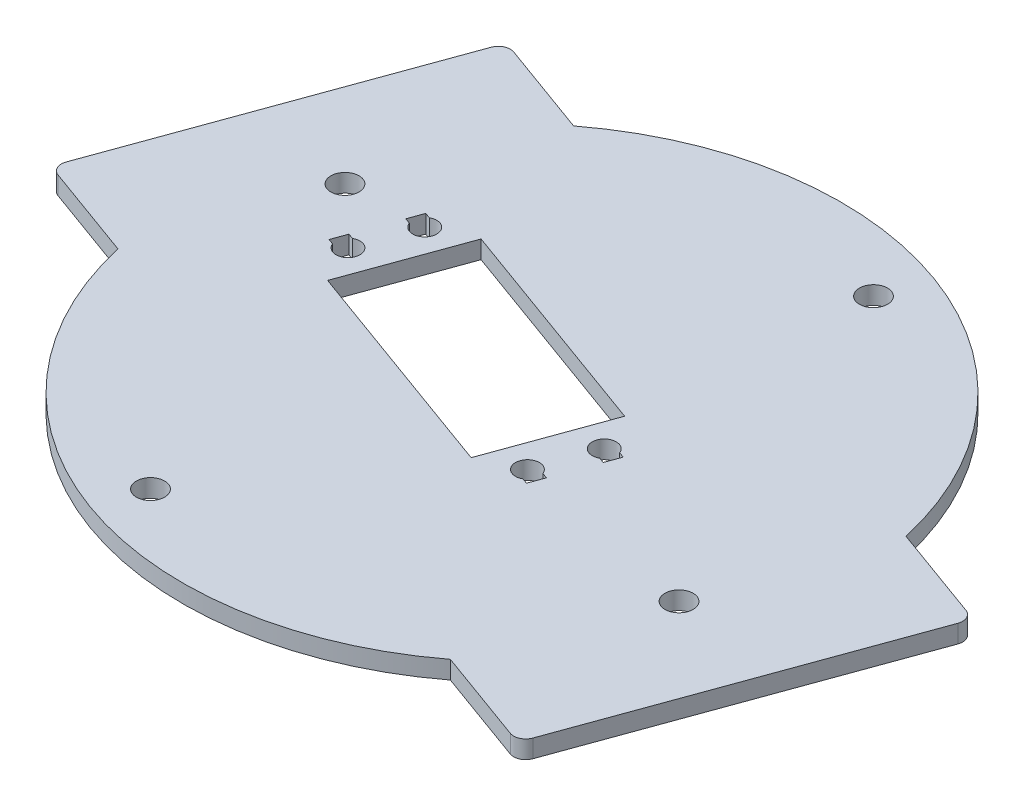
SolidWorks part; units mm, degrees
ref_plane "前视基准面" through (0, 0, 0) normal (0, 0, 1) x (1, 0, 0)
ref_plane "上视基准面" through (0, 0, 0) normal (0, 1, 0) x (1, 0, 0)
ref_plane "右视基准面" through (0, 0, 0) normal (1, 0, 0) x (0, 0, -1)
sketch "草图1" [suppressed] plane through (0, 0, 0) normal (0, 1, 0) x (1, 0, 0)
  circle A0 centre (0, 0) radius 40
  dimension "D1" = 80
sketch "草图2" [suppressed] plane through (0, 0, 0) normal (0, 1, 0) x (1, 0, 0)
  line L0 (-65, 27.6831) -> (-65, -27.6831)
  line L1 (-63, -29.6831) -> (-46.3024, -29.6831)
  line L2 (46.3024, -29.6831) -> (63, -29.6831)
  line L3 (65, -27.6831) -> (65, 27.6831)
  line L4 (63, 29.6831) -> (46.3024, 29.6831)
  line L5 (-46.3024, 29.6831) -> (-63, 29.6831)
  line L6 (37.5, -3.7) -> (37.5, 3.7)
  line L7 (37.5, 3.7) -> (36.5199, 3.7)
  line L8 (36.5199, 6.3) -> (37.5, 6.3)
  line L9 (37.5, 6.3) -> (37.5, 10)
  line L10 (37.5, 10) -> (29, 10)
  line L11 (30, 9) -> (30, -9)
  line L12 (29, -10) -> (37.5, -10)
  line L13 (37.5, -10) -> (37.5, -6.3)
  line L14 (37.5, -6.3) -> (36.5199, -6.3)
  line L15 (36.5199, -3.7) -> (37.5, -3.7)
  line L16 (-17.5, 3.7) -> (-17.5, -3.7)
  line L17 (-17.5, -3.7) -> (-16.5199, -3.7)
  line L18 (-16.5199, -6.3) -> (-17.5, -6.3)
  line L19 (-17.5, -6.3) -> (-17.5, -10)
  line L20 (-17.5, -10) -> (-9, -10)
  line L21 (-10, -9) -> (-10, 9)
  line L22 (-9, 10) -> (-17.5, 10)
  line L23 (-17.5, 10) -> (-17.5, 6.3)
  line L24 (-17.5, 6.3) -> (-16.5199, 6.3)
  line L25 (-16.5199, 3.7) -> (-17.5, 3.7)
  line L26 (0, 0) -> (0, 93.1716)
  arc A0 (-65, -27.6831) -> (-63, -29.6831) centre (-63, -27.6831) ccw
  arc A1 (-46.3024, -29.6831) -> (46.3024, -29.6831) centre (0, 0) ccw
  arc A2 (63, -29.6831) -> (65, -27.6831) centre (63, -27.6831) ccw
  arc A3 (65, 27.6831) -> (63, 29.6831) centre (63, 27.6831) ccw
  arc A4 (46.3024, 29.6831) -> (-46.3024, 29.6831) centre (0, 0) ccw
  arc A5 (-63, 29.6831) -> (-65, 27.6831) centre (-63, 27.6831) ccw
  arc A6 (36.5199, 6.3) -> (36.5199, 3.7) centre (35, 5) ccw
  arc A7 (30, 9) -> (29, 10) centre (29, 9) ccw
  arc A8 (29, -10) -> (30, -9) centre (29, -9) ccw
  arc A9 (36.5199, -3.7) -> (36.5199, -6.3) centre (35, -5) ccw
  arc A10 (-13, -5) -> (-16.5199, -3.7) centre (-15, -5) ccw
  arc A11 (-16.5199, -6.3) -> (-13, -5) centre (-15, -5) ccw
  arc A12 (-10, -9) -> (-9, -10) centre (-9, -9) ccw
  arc A13 (-9, 10) -> (-10, 9) centre (-9, 9) ccw
  arc A14 (-13, 5) -> (-16.5199, 6.3) centre (-15, 5) ccw
  arc A15 (-16.5199, 3.7) -> (-13, 5) centre (-15, 5) ccw
  circle A16 centre (-46.0842, 9.2327) radius 2.35
  circle A17 centre (9.2327, 46.0842) radius 2.35
  circle A18 centre (46.0842, -9.2327) radius 2.35
  circle A19 centre (-9.2327, -46.0842) radius 2.35
  circle A20 centre (0, 0) radius 47
  circle A21 centre (0, 46.5858) radius 2.35
  dimension "D1" = 4.7
  dimension "D2" = 4.7
sketch "草图3" [suppressed] plane through (0, 0, 0) normal (0, 1, 0) x (1, 0, 0)
  circle A0 centre (0, 46.5858) radius 2.35 construction
  circle A1 centre (0, 46.5858) radius 2.35
  circle A2 centre (46.5858, 0) radius 2.35
  circle A3 centre (0, -46.5858) radius 2.35
  circle A4 centre (-46.5858, 0) radius 2.35
  point P12 (0, 0)
  dimension "D1" = 4
sketch "草图4" [suppressed] plane through (0, 0, 0) normal (0, 1, 0) x (1, 0, 0)
  line L1 (30, 9) -> (29, 9)
  line L2 (30, 9) -> (30, 10)
  line L3 (30, 10) -> (29, 10)
  line L4 (29, 9) -> (29, 10)
  line L5 (30, -9) -> (29, -9)
  line L6 (30, -9) -> (30, -10)
  line L7 (30, -10) -> (29, -10)
  line L8 (29, -9) -> (29, -10)
  line L9 (-10, -9) -> (-9, -9)
  line L10 (-10, -9) -> (-10, -10)
  line L11 (-10, -10) -> (-9, -10)
  line L12 (-9, -9) -> (-9, -10)
  line L13 (-10, 9) -> (-9, 9)
  line L14 (-10, 9) -> (-10, 10)
  line L15 (-10, 10) -> (-9, 10)
  line L16 (-9, 9) -> (-9, 10)
  line L17 (30, 10) -> (-10, 10)
  line L18 (30, 10) -> (30, -10)
  line L19 (30, -10) -> (-10, -10)
  line L20 (-10, 10) -> (-10, -10)
sketch "草图5" [suppressed] plane through (0, 0, 0) normal (0, 1, 0) x (1, 0, 0)
  line L0 (-10, 9) -> (-10, 10) construction
  line L1 (-10, -9) -> (-10, 9) construction
  line L2 (-10, -9) -> (-10, -10) construction
  line L3 (30, -10) -> (-10, -10) construction
  line L4 (30, -9) -> (30, -10) construction
  line L5 (30, 10) -> (-10, 10) construction
  line L6 (30, 9) -> (30, -9) construction
  line L7 (30, 9) -> (30, 10) construction
  line L8 (-46.3024, 29.6831) -> (-63, 29.6831) construction
  line L9 (-65, 27.6831) -> (-65, -27.6831) construction
  line L10 (-63, -29.6831) -> (-46.3024, -29.6831) construction
  line L11 (46.3024, -29.6831) -> (63, -29.6831) construction
  line L12 (65, -27.6831) -> (65, 27.6831) construction
  line L13 (63, 29.6831) -> (46.3024, 29.6831) construction
  line L14 (-10, 9) -> (-10, 10)
  line L15 (-10, -9) -> (-10, 9)
  line L16 (-10, -9) -> (-10, -10)
  line L17 (30, -10) -> (-10, -10)
  line L18 (30, -9) -> (30, -10)
  line L19 (30, 10) -> (-10, 10)
  line L20 (30, 9) -> (30, -9)
  line L21 (30, 9) -> (30, 10)
  line L22 (-46.3024, 29.6831) -> (-63, 29.6831)
  line L23 (-65, 27.6831) -> (-65, -27.6831)
  line L24 (-63, -29.6831) -> (-46.3024, -29.6831)
  line L25 (46.3024, -29.6831) -> (63, -29.6831)
  line L26 (65, -27.6831) -> (65, 27.6831)
  line L27 (63, 29.6831) -> (46.3024, 29.6831)
  arc A0 (-63, 29.6831) -> (-65, 27.6831) centre (-63, 27.6831) ccw construction
  arc A1 (-65, -27.6831) -> (-63, -29.6831) centre (-63, -27.6831) ccw construction
  arc A2 (-46.3024, -29.6831) -> (46.3024, -29.6831) centre (0, 0) ccw construction
  arc A3 (63, -29.6831) -> (65, -27.6831) centre (63, -27.6831) ccw construction
  arc A4 (65, 27.6831) -> (63, 29.6831) centre (63, 27.6831) ccw construction
  arc A5 (46.3024, 29.6831) -> (-46.3024, 29.6831) centre (0, 0) ccw construction
  arc A10 (-63, 29.6831) -> (-65, 27.6831) centre (-63, 27.6831) ccw
  arc A11 (-65, -27.6831) -> (-63, -29.6831) centre (-63, -27.6831) ccw
  arc A12 (-46.3024, -29.6831) -> (46.3024, -29.6831) centre (0, 0) ccw
  arc A13 (63, -29.6831) -> (65, -27.6831) centre (63, -27.6831) ccw
  arc A14 (65, 27.6831) -> (63, 29.6831) centre (63, 27.6831) ccw
  arc A15 (46.3024, 29.6831) -> (-46.3024, 29.6831) centre (0, 0) ccw
extrude "凸台-拉伸1" [suppressed] add sketch "草图5" along normal blind 5
sketch "草图8" plane through (0, 0, 0) normal (0, 1, 0) x (1, 0, 0)
  line L0 (5.9908, -12.8106) -> (-31.6119, 0.829)
  line L1 (-38.6624, 3.3864) -> (-30.6718, 0.488)
  line L2 (13.0413, -15.368) -> (5.0507, -12.4696)
  line L3 (-33.4058, 43.6927) -> (-49.1026, 49.3864)
  line L4 (-51.6647, 48.1883) -> (-70.544, -3.8597)
  line L5 (-69.3459, -6.4218) -> (-53.649, -12.1155)
  line L6 (33.4058, -43.6927) -> (49.1026, -49.3864)
  line L7 (51.6647, -48.1883) -> (70.544, 3.8597)
  line L8 (69.3459, 6.4218) -> (53.649, 12.1155)
  line L9 (-24.7921, 19.6303) -> (-31.6119, 0.829)
  line L10 (-31.6119, 0.829) -> (5.9908, -12.8106)
  line L11 (14.2681, -9.1113) -> (15.1895, -9.4456)
  line L12 (15.1895, -9.4456) -> (17.7128, -2.4891)
  line L13 (17.7128, -2.4891) -> (16.7914, -2.1548)
  line L14 (17.678, 0.2893) -> (18.5994, -0.0449)
  line L15 (18.5994, -0.0449) -> (19.8611, 3.4334)
  line L16 (19.8611, 3.4334) -> (12.8106, 5.9908)
  line L17 (12.8106, 5.9908) -> (5.9908, -12.8106)
  line L18 (5.9908, -12.8106) -> (13.0413, -15.368)
  line L19 (13.0413, -15.368) -> (14.3029, -11.8897)
  line L20 (14.3029, -11.8897) -> (13.3816, -11.5555)
  line L21 (5.9908, -12.8106) -> (12.8106, 5.9908)
  line L22 (12.8106, 5.9908) -> (-24.7921, 19.6303)
  line L23 (-33.0695, 15.9311) -> (-33.9909, 16.2653)
  line L24 (-33.9909, 16.2653) -> (-36.5142, 9.3088)
  line L25 (-36.5142, 9.3088) -> (-35.5928, 8.9746)
  line L26 (-36.4794, 6.5304) -> (-37.4008, 6.8647)
  line L27 (-37.4008, 6.8647) -> (-38.6624, 3.3864)
  line L28 (-38.6624, 3.3864) -> (-31.6119, 0.829)
  line L29 (-31.6119, 0.829) -> (-24.7921, 19.6303)
  line L30 (-24.7921, 19.6303) -> (-31.8426, 22.1878)
  line L31 (-31.8426, 22.1878) -> (-33.1043, 18.7095)
  line L32 (-33.1043, 18.7095) -> (-32.1829, 18.3753)
  circle A0 centre (-44.1093, 16.2285) radius 2.35
  circle A1 centre (16.2285, 44.1093) radius 2.35
  circle A2 centre (44.1093, -16.2285) radius 2.35
  arc A3 (53.649, 12.1155) -> (-33.4058, 43.6927) centre (0, 0) ccw
  arc A4 (-49.1026, 49.3864) -> (-51.6647, 48.1883) centre (-49.7846, 47.5063) ccw
  arc A5 (-70.544, -3.8597) -> (-69.3459, -6.4218) centre (-68.6639, -4.5417) ccw
  arc A6 (-53.649, -12.1155) -> (33.4058, -43.6927) centre (0, 0) ccw
  arc A7 (49.1026, -49.3864) -> (51.6647, -48.1883) centre (49.7846, -47.5063) ccw
  arc A8 (70.544, 3.8597) -> (69.3459, 6.4218) centre (68.6639, 4.5417) ccw
  circle A9 centre (-16.2285, -44.1093) radius 2.35
  arc A10 (14.2681, -9.1113) -> (10.5159, -9.1332) centre (12.3961, -9.8152) ccw
  arc A11 (13.9258, 0.2675) -> (16.7914, -2.1548) centre (15.806, -0.4145) ccw
  arc A12 (17.678, 0.2893) -> (13.9258, 0.2675) centre (15.806, -0.4145) ccw
  arc A13 (10.5159, -9.1332) -> (13.3816, -11.5555) centre (12.3961, -9.8152) ccw
  arc A14 (-33.0695, 15.9311) -> (-32.1829, 18.3753) centre (-31.1974, 16.6349) ccw
  arc A15 (-36.4794, 6.5304) -> (-35.5928, 8.9746) centre (-34.6073, 7.2343) ccw
  point P63 (0, 0)
sketch "草图10" plane through (0, 0, 0) normal (0, 1, 0) x (1, 0, 0)
  line L0 (33.4058, -43.6927) -> (49.1026, -49.3864) construction
  line L1 (-69.3459, -6.4218) -> (-53.649, -12.1155) construction
  line L2 (-51.6647, 48.1883) -> (-70.544, -3.8597) construction
  line L3 (-33.4058, 43.6927) -> (-49.1026, 49.3864) construction
  line L4 (51.6647, -48.1883) -> (70.544, 3.8597) construction
  line L5 (69.3459, 6.4218) -> (53.649, 12.1155) construction
  line L6 (33.4058, -43.6927) -> (49.1026, -49.3864)
  line L7 (-69.3459, -6.4218) -> (-53.649, -12.1155)
  line L8 (-51.6647, 48.1883) -> (-70.544, -3.8597)
  line L9 (-33.4058, 43.6927) -> (-49.1026, 49.3864)
  line L10 (51.6647, -48.1883) -> (70.544, 3.8597)
  line L11 (69.3459, 6.4218) -> (53.649, 12.1155)
  circle A0 centre (16.2285, 44.1093) radius 2.35 construction
  circle A1 centre (-44.1093, 16.2285) radius 2.35 construction
  circle A2 centre (-16.2285, -44.1093) radius 2.35 construction
  circle A3 centre (44.1093, -16.2285) radius 2.35 construction
  arc A4 (49.1026, -49.3864) -> (51.6647, -48.1883) centre (49.7846, -47.5063) ccw construction
  arc A5 (-53.649, -12.1155) -> (33.4058, -43.6927) centre (0, 0) ccw construction
  arc A6 (-70.544, -3.8597) -> (-69.3459, -6.4218) centre (-68.6639, -4.5417) ccw construction
  arc A7 (-49.1026, 49.3864) -> (-51.6647, 48.1883) centre (-49.7846, 47.5063) ccw construction
  arc A8 (53.649, 12.1155) -> (-33.4058, 43.6927) centre (0, 0) ccw construction
  arc A9 (70.544, 3.8597) -> (69.3459, 6.4218) centre (68.6639, 4.5417) ccw construction
  circle A10 centre (16.2285, 44.1093) radius 2.35
  circle A11 centre (-44.1093, 16.2285) radius 2.35
  circle A12 centre (-16.2285, -44.1093) radius 2.35
  circle A13 centre (44.1093, -16.2285) radius 2.35
  arc A14 (49.1026, -49.3864) -> (51.6647, -48.1883) centre (49.7846, -47.5063) ccw
  arc A15 (-53.649, -12.1155) -> (33.4058, -43.6927) centre (0, 0) ccw
  arc A16 (-70.544, -3.8597) -> (-69.3459, -6.4218) centre (-68.6639, -4.5417) ccw
  arc A17 (-49.1026, 49.3864) -> (-51.6647, 48.1883) centre (-49.7846, 47.5063) ccw
  arc A18 (53.649, 12.1155) -> (-33.4058, 43.6927) centre (0, 0) ccw
  arc A19 (70.544, 3.8597) -> (69.3459, 6.4218) centre (68.6639, 4.5417) ccw
extrude "凸台-拉伸2" add sketch "草图10" along normal blind 3
sketch "草图11" plane through (0, 0, 0) normal (0, 1, 0) x (1, 0, 0)
  line L0 (14.2681, -9.1113) -> (15.1895, -9.4456) construction
  line L1 (14.3029, -11.8897) -> (13.3816, -11.5555) construction
  line L2 (14.3029, -11.8897) -> (13.3816, -11.5555)
  line L3 (14.2681, -9.1113) -> (15.1895, -9.4456)
  line L4 (17.678, 0.2893) -> (18.5994, -0.0449) construction
  line L5 (17.7128, -2.4891) -> (16.7914, -2.1548) construction
  line L6 (17.678, 0.2893) -> (18.5994, -0.0449)
  line L7 (17.7128, -2.4891) -> (16.7914, -2.1548)
  line L8 (-33.1043, 18.7095) -> (-32.1829, 18.3753) construction
  line L9 (-33.0695, 15.9311) -> (-33.9909, 16.2653) construction
  line L10 (-36.5142, 9.3088) -> (-35.5928, 8.9746) construction
  line L11 (-36.4794, 6.5304) -> (-37.4008, 6.8647) construction
  line L12 (-33.1043, 18.7095) -> (-32.1829, 18.3753)
  line L13 (-33.0695, 15.9311) -> (-33.9909, 16.2653)
  line L14 (-36.5142, 9.3088) -> (-35.5928, 8.9746)
  line L15 (-36.4794, 6.5304) -> (-37.4008, 6.8647)
  line L16 (-24.7921, 19.6303) -> (-31.6119, 0.829) construction
  line L17 (5.9908, -12.8106) -> (-31.6119, 0.829) construction
  line L18 (12.8106, 5.9908) -> (5.9908, -12.8106) construction
  line L19 (12.8106, 5.9908) -> (-24.7921, 19.6303) construction
  line L20 (-24.7921, 19.6303) -> (-31.6119, 0.829)
  line L21 (5.9908, -12.8106) -> (-31.6119, 0.829)
  line L22 (12.8106, 5.9908) -> (5.9908, -12.8106)
  line L23 (12.8106, 5.9908) -> (-24.7921, 19.6303)
  line L24 (14.3029, -11.8897) -> (15.1895, -9.4456)
  line L25 (17.7128, -2.4891) -> (18.5994, -0.0449)
  line L26 (-37.4008, 6.8647) -> (-36.5142, 9.3088)
  line L27 (-33.9909, 16.2653) -> (-33.1043, 18.7095)
  arc A0 (10.5159, -9.1332) -> (13.3816, -11.5555) centre (12.3961, -9.8152) ccw construction
  arc A1 (14.2681, -9.1113) -> (10.5159, -9.1332) centre (12.3961, -9.8152) ccw construction
  arc A2 (14.2681, -9.1113) -> (10.5159, -9.1332) centre (12.3961, -9.8152) ccw
  arc A3 (10.5159, -9.1332) -> (13.3816, -11.5555) centre (12.3961, -9.8152) ccw
  arc A4 (17.678, 0.2893) -> (13.9258, 0.2675) centre (15.806, -0.4145) ccw construction
  arc A5 (13.9258, 0.2675) -> (16.7914, -2.1548) centre (15.806, -0.4145) ccw construction
  arc A6 (17.678, 0.2893) -> (13.9258, 0.2675) centre (15.806, -0.4145) ccw
  arc A7 (13.9258, 0.2675) -> (16.7914, -2.1548) centre (15.806, -0.4145) ccw
  arc A8 (-33.0695, 15.9311) -> (-32.1829, 18.3753) centre (-31.1974, 16.6349) ccw construction
  arc A9 (-36.4794, 6.5304) -> (-35.5928, 8.9746) centre (-34.6073, 7.2343) ccw construction
  arc A10 (-33.0695, 15.9311) -> (-32.1829, 18.3753) centre (-31.1974, 16.6349) ccw
  arc A11 (-36.4794, 6.5304) -> (-35.5928, 8.9746) centre (-34.6073, 7.2343) ccw
extrude "切除-拉伸3" cut sketch "草图11" along normal up to surface (3 mm away) up to face at (-16.2285, 3, 46.4593)
ref_plane "基准面1" through (0, 3, 0) normal (0, 1, 0) x (1, 0, 0)
sketch "草图12" plane through (0, 3, 0) normal (0, 1, 0) x (1, 0, 0)
  line L3 (-32.1829, 18.3753) -> (-33.1043, 18.7095) construction
  line L4 (-33.1043, 18.7095) -> (-33.9909, 16.2653) construction
  line L5 (-33.9909, 16.2653) -> (-33.0695, 15.9311) construction
  line L6 (51.6647, -48.1883) -> (70.544, 3.8597)
  line L7 (69.3459, 6.4218) -> (53.649, 12.1155)
  line L8 (-33.4058, 43.6927) -> (-49.1026, 49.3864)
  line L9 (-51.6647, 48.1883) -> (-70.544, -3.8597)
  line L10 (-69.3459, -6.4218) -> (-53.649, -12.1155)
  line L11 (33.4058, -43.6927) -> (49.1026, -49.3864)
  line L12 (51.6647, -48.1883) -> (70.544, 3.8597)
  line L13 (69.3459, 6.4218) -> (53.649, 12.1155)
  line L14 (-33.4058, 43.6927) -> (-49.1026, 49.3864)
  line L15 (-51.6647, 48.1883) -> (-70.544, -3.8597)
  line L16 (-69.3459, -6.4218) -> (-53.649, -12.1155)
  line L17 (33.4058, -43.6927) -> (49.1026, -49.3864)
  line L18 (-33.9909, 16.2653) -> (-33.0695, 15.9311)
  line L19 (-32.1829, 18.3753) -> (-33.1043, 18.7095)
  line L20 (-33.1043, 18.7095) -> (-33.9909, 16.2653)
  line L21 (-37.4008, 6.8647) -> (-36.4794, 6.5304) construction
  line L22 (-36.5142, 9.3088) -> (-37.4008, 6.8647) construction
  line L23 (-35.5928, 8.9746) -> (-36.5142, 9.3088) construction
  line L24 (-37.4008, 6.8647) -> (-36.4794, 6.5304)
  line L25 (-36.5142, 9.3088) -> (-37.4008, 6.8647)
  line L26 (-35.5928, 8.9746) -> (-36.5142, 9.3088)
  line L27 (16.7914, -2.1548) -> (17.7128, -2.4891) construction
  line L28 (17.7128, -2.4891) -> (18.5994, -0.0449) construction
  line L29 (18.5994, -0.0449) -> (17.678, 0.2893) construction
  line L30 (16.7914, -2.1548) -> (17.7128, -2.4891)
  line L31 (17.7128, -2.4891) -> (18.5994, -0.0449)
  line L32 (18.5994, -0.0449) -> (17.678, 0.2893)
  circle A0 centre (16.2285, 44.1093) radius 2.35 construction
  circle A1 centre (16.2285, 44.1093) radius 2.35
  circle A3 centre (44.1093, -16.2285) radius 2.35 construction
  circle A5 centre (44.1093, -16.2285) radius 2.35
  arc A6 (49.1026, -49.3864) -> (51.6647, -48.1883) centre (49.7846, -47.5063) ccw
  arc A7 (70.544, 3.8597) -> (69.3459, 6.4218) centre (68.6639, 4.5417) ccw
  arc A8 (53.649, 12.1155) -> (-33.4058, 43.6927) centre (0, 0) ccw
  arc A9 (-49.1026, 49.3864) -> (-51.6647, 48.1883) centre (-49.7846, 47.5063) ccw
  arc A10 (-70.544, -3.8597) -> (-69.3459, -6.4218) centre (-68.6639, -4.5417) ccw
  arc A11 (-53.649, -12.1155) -> (33.4058, -43.6927) centre (0, 0) ccw
  arc A12 (49.1026, -49.3864) -> (51.6647, -48.1883) centre (49.7846, -47.5063) ccw
  arc A13 (70.544, 3.8597) -> (69.3459, 6.4218) centre (68.6639, 4.5417) ccw
  arc A14 (53.649, 12.1155) -> (-33.4058, 43.6927) centre (0, 0) ccw
  arc A15 (-49.1026, 49.3864) -> (-51.6647, 48.1883) centre (-49.7846, 47.5063) ccw
  arc A16 (-70.544, -3.8597) -> (-69.3459, -6.4218) centre (-68.6639, -4.5417) ccw
  arc A17 (-53.649, -12.1155) -> (33.4058, -43.6927) centre (0, 0) ccw
  circle A18 centre (-16.2285, -44.1093) radius 2.35 construction
  circle A19 centre (-16.2285, -44.1093) radius 2.35
  circle A20 centre (-44.1093, 16.2285) radius 2.35 construction
  circle A21 centre (-44.1093, 16.2285) radius 2.35
  arc A22 (-33.0695, 15.9311) -> (-32.1829, 18.3753) centre (-31.1974, 16.6349) ccw construction
  arc A23 (-33.0695, 15.9311) -> (-32.1829, 18.3753) centre (-31.1974, 16.6349) ccw
  arc A24 (-36.4794, 6.5304) -> (-35.5928, 8.9746) centre (-34.6073, 7.2343) ccw construction
  arc A25 (-36.4794, 6.5304) -> (-35.5928, 8.9746) centre (-34.6073, 7.2343) ccw
  arc A26 (17.678, 0.2893) -> (16.7914, -2.1548) centre (15.806, -0.4145) ccw construction
  arc A27 (17.678, 0.2893) -> (16.7914, -2.1548) centre (15.806, -0.4145) ccw
  dimension "D1" = 0
